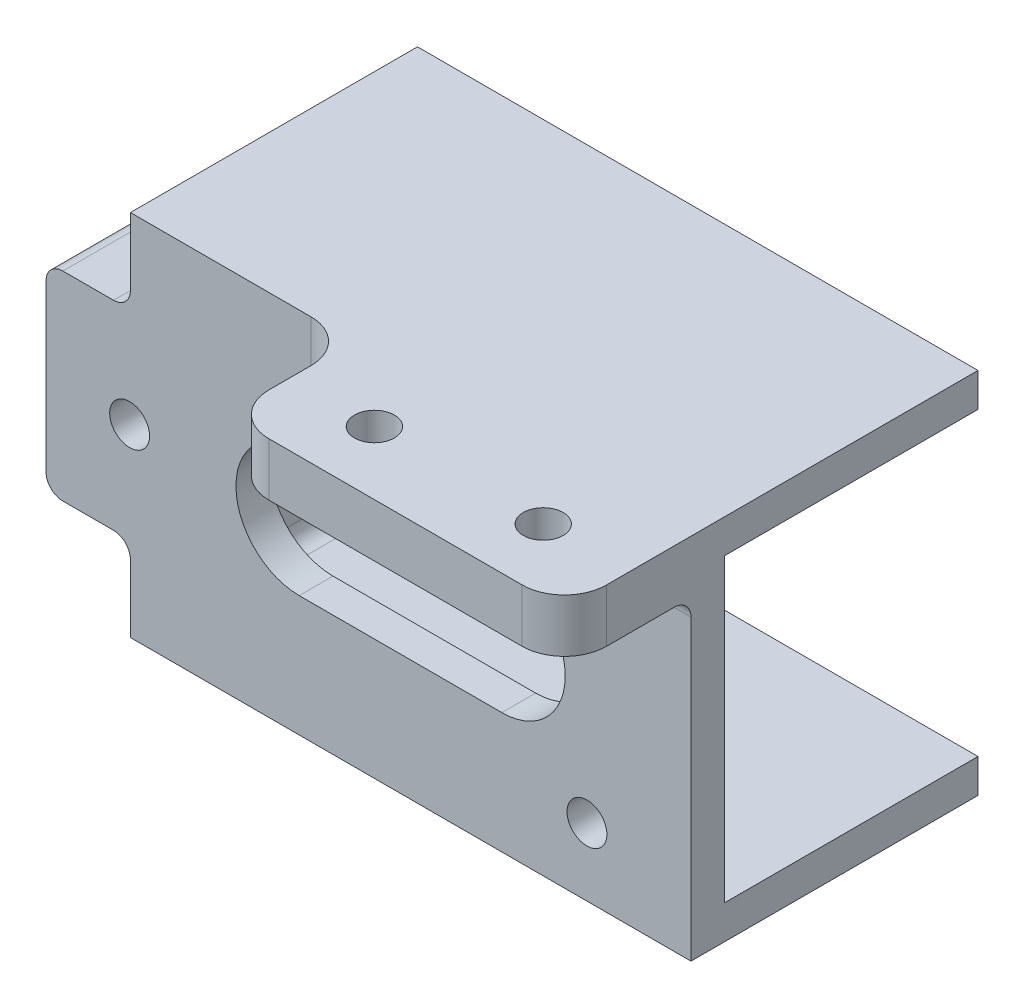
SolidWorks part; units mm, degrees
ref_plane "Front Plane" through (0, 0, 0) normal (0, 0, 1) x (1, 0, 0)
ref_plane "Top Plane" through (0, 0, 0) normal (0, 1, 0) x (1, 0, 0)
ref_plane "Right Plane" through (0, 0, 0) normal (1, 0, 0) x (0, 0, -1)
sketch "Sketch1" plane through (0, 0, 0) normal (0, 0, 1) x (1, 0, 0)
  line L0 (-2.54, 25.146) -> (39.624, 25.146)
  line L1 (0, 0) -> (37.084, 0)
  line L2 (0, 0) -> (0, 22.606)
  line L3 (0, 22.606) -> (37.084, 22.606)
  line L5 (39.624, -2.54) -> (39.624, 0)
  line L6 (-2.54, -2.54) -> (39.624, -2.54)
  line L7 (-2.54, -2.54) -> (-2.54, 25.146)
  line L8 (37.084, 0) -> (37.084, 22.606) construction
  line L9 (37.084, 22.606) -> (39.624, 22.606)
  line L10 (37.084, 0) -> (39.624, 0)
  line L11 (39.624, 22.606) -> (39.624, 25.146)
  line L12 (39.624, -2.54) -> (39.624, 25.146) construction
  dimension "D1" = 22.606
  dimension "D2" = 37.084
  dimension "D3" = 2.54
extrude "Boss-Extrude1" add sketch "Sketch1" along normal blind 19.05
sketch "Sketch2" plane through (0, 0, 19.05) normal (0, 0, 1) x (1, 0, 0)
  line L1 (-2.54, 25.146) -> (39.624, 25.146)
  line L2 (-2.54, 25.146) -> (-2.54, -2.54)
  line L3 (-2.54, -2.54) -> (39.624, -2.54)
  line L4 (39.624, 25.146) -> (39.624, -2.54)
extrude "Boss-Extrude2" add sketch "Sketch2" along normal blind 2.54
sketch "Sketch3" plane through (-2.54, 0, 0) normal (-1, 0, 0) x (0, 0, 1)
  line L1 (21.59, 18.796) -> (11.19, 18.796)
  line L2 (21.59, 18.796) -> (21.59, 3.81)
  line L3 (21.59, 3.81) -> (11.19, 3.81)
  line L4 (11.19, 18.796) -> (11.19, 3.81)
  line L5 (21.59, 25.146) -> (0, 25.146) construction
  line L6 (21.59, 25.146) -> (21.59, -2.54) construction
  line L7 (21.59, -2.54) -> (0, -2.54) construction
  dimension "D1" = 6.35
  dimension "D2" = 10.4
  dimension "D3" = 6.35
extrude "Boss-Extrude3" add sketch "Sketch3" along normal blind 6.35
sketch "Sketch4" plane through (0, 0, 11.19) normal (0, 0, -1) x (-1, 0, 0)
  line L1 (8.89, 18.796) -> (8.89, 3.81) construction
  line L2 (2.54, 25.146) -> (2.54, -2.54) construction
  circle A0 centre (2.6, 11.303) radius 1.5
  point P6 (8.89, 11.303)
  dimension "D1" = 3
  dimension "D2" = 0.06
extrude "Cut-Extrude1" cut sketch "Sketch4" against normal through all both and the other way through all
fillet "Fillet2" radius 1.27 4 edges at (-8.89, 3.81, 16.39) (-2.54, 3.81, 16.39) (-2.54, 18.796, 16.39) (-8.89, 18.796, 16.39)
sketch "Sketch5" plane through (0, 0, 21.59) normal (0, 0, 1) x (1, 0, 0)
  line L0 (39.624, -2.54) -> (39.624, 25.146) construction
  line L1 (-2.54, 20.066) -> (-2.54, 2.54) construction
  line L2 (10.16, 16.0655) -> (25.4, 16.0655)
  line L3 (10.16, 6.5405) -> (25.4, 6.5405)
  circle A0 centre (10.16, 11.303) radius 4.7625
  circle A1 centre (25.4, 11.303) radius 4.7625
  point P5 (39.624, 11.303)
  dimension "D1" = 9.525
  dimension "D2" = 12.7
  dimension "D3" = 15.24
extrude "Cut-Extrude2" cut sketch "Sketch5" against normal through all both contours A0 | A1 L2 A0 L3 | A1
sketch "Sketch6" plane through (0, 0, 21.59) normal (0, 0, 1) x (1, 0, 0)
  line L0 (39.624, 25.146) -> (-2.54, 25.146) construction
  line L1 (14.224, 25.146) -> (39.624, 25.146)
  line L2 (14.224, 25.146) -> (14.224, 21.146)
  line L3 (14.224, 21.146) -> (39.624, 21.146)
  line L4 (39.624, 25.146) -> (39.624, 21.146)
  line L7 (39.624, -2.54) -> (39.624, 25.146) construction
  point P6 (26.924, 21.146)
  dimension "D1" = 4
  dimension "D2" = 25.4
  dimension "D3" = 12.7
extrude "Boss-Extrude4" add sketch "Sketch6" along normal blind 9.525
fillet "Fillet3" radius 3.175 3 edges at (39.624, 23.146, 31.115) (14.224, 23.146, 31.115) (14.224, 23.146, 21.59)
fillet "Fillet4" radius 1.27 1 edges at (25.3365, 21.146, 21.59)
fillet "Fillet6" radius 1.27 2 edges at (0, 0, 9.525) (0, 22.606, 9.525)
sketch "Sketch8" plane through (0, 25.146, 0) normal (0, 1, 0) x (1, 0, 0)
  line L1 (14.224, -24.765) -> (14.224, -21.59) construction
  line L2 (26.924, -21.59) -> (26.924, -31.115) construction
  line L3 (36.449, -31.115) -> (17.399, -31.115) construction
  line L4 (14.224, -21.59) -> (26.924, -21.59) construction
  line L5 (26.924, -21.59) -> (39.624, -21.59) construction
  circle A0 centre (20.574, -26.3525) radius 1.5
  circle A1 centre (33.274, -26.3525) radius 1.5
  point P14 (26.924, -26.3525)
  point P15 (33.274, -21.59)
  point P16 (20.574, -21.59)
  dimension "D1" = 3
  dimension "D2" = 3
extrude "Cut-Extrude3" cut sketch "Sketch8" against normal through all both
sketch "Sketch9" plane through (0, 0, 0) normal (0, 0, -1) x (-1, 0, 0)
  line L0 (0, 1.27) -> (0, 21.336) construction
  line L1 (0, 16.383) -> (2.54, 16.383)
  line L2 (0, 16.383) -> (0, 6.223)
  line L3 (0, 6.223) -> (2.54, 6.223)
  line L4 (2.54, 16.383) -> (2.54, 6.223)
  line L5 (2.54, 20.066) -> (2.54, 12.8018) construction
  point P8 (0, 11.303)
  dimension "D1" = 10.16
extrude "Cut-Extrude4" cut sketch "Sketch9" against normal up to surface (11.19 mm away) up to face at (-5.236, 11.303, 11.19)
sketch "Sketch10" plane through (0, 0, 19.05) normal (0, 0, -1) x (-1, 0, 0)
  line L1 (-39.624, 0) -> (-1.27, 0) construction
  line L2 (0, 1.27) -> (0, 21.336) construction
  circle A0 centre (-31.8, 2.55) radius 1.5
  point P8 (0, 0)
  dimension "D1" = 3
  dimension "D2" = 31.8
  dimension "D3" = 2.55
extrude "Cut-Extrude5" cut sketch "Sketch10" against normal through all both and the other way through all
